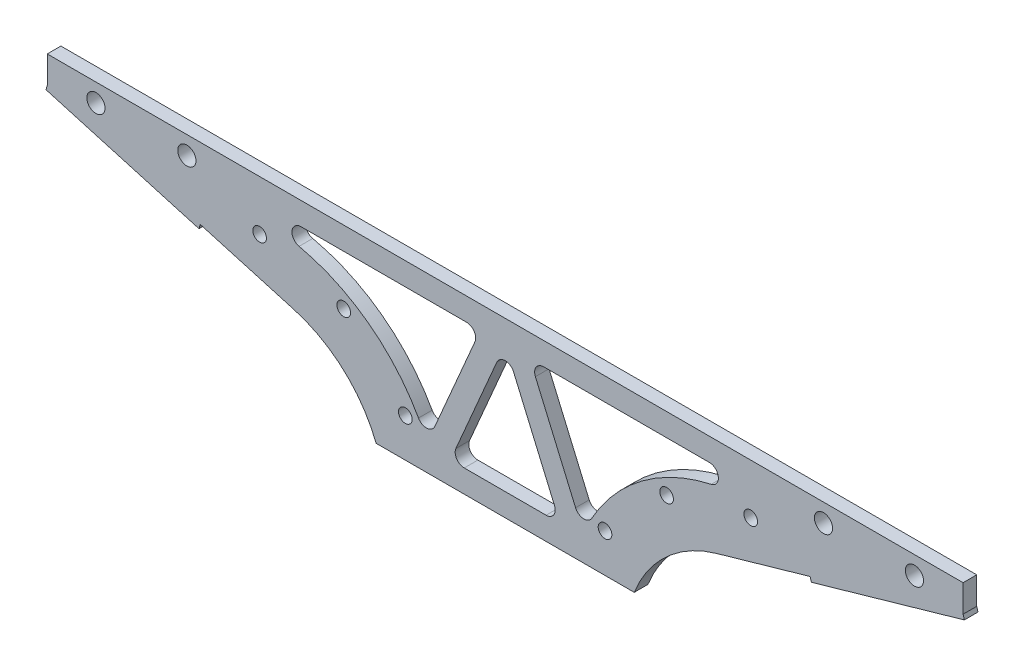
SolidWorks part; units mm, degrees
material "Thornel Mat VMA"
ref_plane "前视基准面" through (0, 0, 0) normal (0, 0, 1) x (1, 0, 0)
ref_plane "上视基准面" through (0, 0, 0) normal (0, 1, 0) x (1, 0, 0)
ref_plane "右视基准面" through (0, 0, 0) normal (1, 0, 0) x (0, 0, -1)
sketch "草图1" plane through (0, 0, 0) normal (0, 0, 1) x (1, 0, 0)
  line L0 (-54, 0) -> (54, 0) construction
  line L1 (0, 0) -> (0, 10) construction
  line L2 (-46.42, 26.4347) -> (-100.7026, 42)
  line L3 (46.42, 26.4347) -> (100.7026, 42)
  line L4 (-28.3826, 10) -> (28.3826, 10)
  line L5 (-100.7026, 42) -> (-100.7026, 48)
  line L6 (-100.7026, 48) -> (100.7026, 48)
  line L7 (100.7026, 48) -> (100.7026, 42)
  line L8 (-90, 44) -> (-70, 44) construction
  line L9 (90, 44) -> (70, 44) construction
  circle A0 centre (-54, 0) radius 26.5 construction
  circle A1 centre (54, 0) radius 26.5 construction
  arc A2 (-28.3826, 10) -> (-46.42, 26.4347) centre (-54, 0) ccw
  arc A3 (28.3826, 10) -> (46.42, 26.4347) centre (54, 0) cw
  circle A4 centre (-54, 0) radius 37 construction
  circle A5 centre (-54, 37) radius 1.5
  circle A6 centre (-35.5, 32.0429) radius 1.5
  circle A7 centre (-21.9571, 18.5) radius 1.5
  circle A8 centre (-17, 0) radius 1.5 construction
  circle A9 centre (17, 0) radius 1.5 construction
  circle A10 centre (21.9571, 18.5) radius 1.5
  circle A11 centre (35.5, 32.0429) radius 1.5
  circle A12 centre (54, 37) radius 1.5
  circle A13 centre (54, 0) radius 37 construction
  circle A14 centre (-90, 44) radius 2
  circle A15 centre (-70, 44) radius 2
  circle A16 centre (70, 44) radius 2
  circle A17 centre (90, 44) radius 2
  point P2 (0, 0)
  dimension "D2" = 53
  dimension "D3" = 55
  dimension "D8" = 74
  dimension "D9" = 3
  dimension "D11" = 20
  dimension "D14" = 4
  dimension "D1" = 108
  dimension "D4" = 16
  dimension "D5" = 10
  dimension "D6" = 6
  dimension "D7" = 38
  dimension "D12" = 70
  dimension "D13" = 4
  dimension "D10" = 4
extrude "凸台-拉伸1" add sketch "草图1" along normal blind 3
sketch "草图2" plane through (0, 0, 3) normal (0, 0, 1) x (1, 0, 0)
  line L0 (-100.7026, 42) -> (-100.9783, 41.0387)
  line L1 (-100.9783, 41.0387) -> (-67.3341, 31.3914)
  line L2 (-67.3341, 31.3914) -> (-67.0585, 32.3527)
  line L3 (-100.7026, 42) -> (-46.42, 26.4347) construction
  line L4 (-67.0585, 32.3527) -> (-100.7026, 42)
  line L5 (0, 10) -> (0, 48) construction
  line L6 (-28.3826, 10) -> (28.3826, 10) construction
  line L7 (100.7026, 48) -> (-100.7026, 48) construction
  line L8 (67.0585, 32.3527) -> (100.7026, 42)
  line L9 (67.3341, 31.3914) -> (67.0585, 32.3527)
  line L10 (100.9783, 41.0387) -> (67.3341, 31.3914)
  line L11 (100.7026, 42) -> (100.9783, 41.0387)
  dimension "D1" = 1
  dimension "D2" = 35
extrude "凸台-拉伸2" add sketch "草图2" against normal up to surface (3 mm away) up to face at (0, 32.1362, 0)
sketch "草图3" plane through (0, 0, 3) normal (0, 0, 1) x (1, 0, 0)
  line L1 (-6.6417, 40.2101) -> (-15.4766, 19.6585)
  line L3 (-10.8374, 17.7899) -> (-1.8374, 38.7258)
  line L4 (1.8374, 38.7258) -> (10.8374, 17.7899)
  line L5 (9, 15) -> (-9, 15)
  line L6 (-44.8896, 43) -> (-8.4792, 43)
  line L7 (100.7026, 48) -> (-100.7026, 48) construction
  line L8 (-28.3826, 10) -> (28.3826, 10) construction
  line L9 (0, 15) -> (0, 10) construction
  line L10 (44.8896, 43) -> (8.4792, 43)
  line L11 (6.6417, 40.2101) -> (15.4766, 19.6585)
  circle A0 centre (-54, 0) radius 40 construction
  arc A1 (-45.3234, 39.0476) -> (-19.0609, 19.4746) centre (-54, 0) cw
  arc A2 (-45.3234, 39.0476) -> (-44.8896, 43) centre (-44.8896, 41) cw
  arc A3 (10.8374, 17.7899) -> (9, 15) centre (9, 17) cw
  arc A4 (-10.8374, 17.7899) -> (-9, 15) centre (-9, 17) ccw
  arc A5 (-1.8374, 38.7258) -> (1.8374, 38.7258) centre (0, 37.9359) cw
  arc A6 (-8.4792, 43) -> (-6.6417, 40.2101) centre (-8.4792, 41) cw
  arc A7 (-19.0609, 19.4746) -> (-15.4766, 19.6585) centre (-17.314, 20.4484) ccw
  arc A8 (45.3234, 39.0476) -> (44.8896, 43) centre (44.8896, 41) ccw
  arc A9 (45.3234, 39.0476) -> (19.0609, 19.4746) centre (54, 0) ccw
  arc A10 (8.4792, 43) -> (6.6417, 40.2101) centre (8.4792, 41) ccw
  arc A11 (19.0609, 19.4746) -> (15.4766, 19.6585) centre (17.314, 20.4484) cw
  point P10 (0, 15)
  point P25 (0, 43)
  dimension "D1" = 80
  dimension "D2" = 5
  dimension "D4" = 2
  dimension "D6" = 2
  dimension "D3" = 5
  dimension "D5" = 5
  dimension "D7" = 18
extrude "切除-拉伸1" cut sketch "草图3" against normal through all
